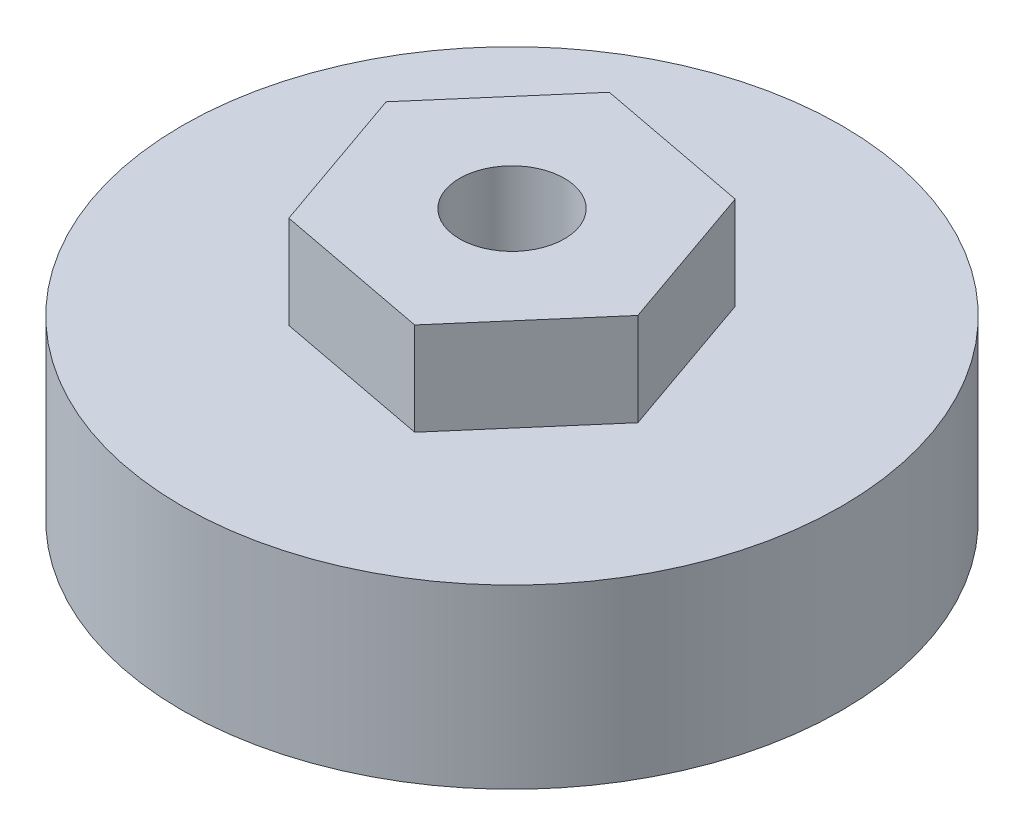
SolidWorks part; units mm, degrees
ref_plane "Front Plane" through (0, 0, 0) normal (0, 0, 1) x (1, 0, 0)
ref_plane "Top Plane" through (0, 0, 0) normal (0, 1, 0) x (1, 0, 0)
ref_plane "Right Plane" through (0, 0, 0) normal (1, 0, 0) x (0, 0, -1)
sketch "Sketch1" plane through (0, 0, 0) normal (0, 1, 0) x (1, 0, 0)
  circle A0 centre (0, 0) radius 11
  dimension "D1" = 22
extrude "Boss-Extrude1" add sketch "Sketch1" along normal blind 9
sketch "Sketch2" plane through (0, 9, 0) normal (0, 1, 0) x (1, 0, 0)
  line L1 (3.4477, 3.9981) -> (-1.7386, 4.9848)
  line L2 (-1.7386, 4.9848) -> (-5.1863, 0.9867)
  line L3 (-5.1863, 0.9867) -> (-3.4477, -3.9981)
  line L4 (-3.4477, -3.9981) -> (1.7386, -4.9848)
  line L5 (1.7386, -4.9848) -> (5.1863, -0.9867)
  line L6 (5.1863, -0.9867) -> (3.4477, 3.9981)
  circle A0 centre (0, 0) radius 4.572 construction
  dimension "D1" = 9.144
extrude "Cut-Extrude1" cut sketch "Sketch2" against normal blind 3.1 flip side to cut
sketch "Sketch3" plane through (0, 9, 0) normal (0, 1, 0) x (1, 0, 0)
  circle A0 centre (0, 0) radius 1.75
  dimension "D1" = 3.5
extrude "Cut-Extrude2" cut sketch "Sketch3" against normal through all
sketch "Sketch4" plane through (0, 5.9, 0) normal (0, 1, 0) x (1, 0, 0)
  point P0 (0, 0)
equation "\"MDF\"= 4.8mm"
equation "\"Foamcore\"= 4.6mm"
equation "\"PCB\" = 1.6mm"
equation "\"GMaterial\"= \"MDF\""
equation "\"BaseWidth\" = 10in"
equation "\"SkidLength\" = 1in"
equation "\"SkidClearance\" = 0.4in"
equation "\"MotorMountLength\" = 2in"
equation "\"MotorMountWidth\" = \"GMaterial\""
equation "\"MotorMountHeight\" = 2.25in"
equation "\"UnoStackWidth\" = 77.4mm"
equation "\"UnoStackLength\" = 79.8mm"
equation "\"UnoStackHeight\" = 34.2mm"
equation "\"TallHexRiserHeight\" = 22.2mm"
equation "\"PingPongBallSize\" = 40mm"
equation "\"BarrelLength\" = 9in"
equation "\"BarrelSize\" = \"PingPongBallSize\""
equation "\"PlatformLength\" = 4in"
equation "\"PlatformWidth\" = 6in"
equation "\"ServoMountHeight\"=2.49223"
equation "\"ServoGearHeight\" = 0.95330261in"
equation "\"ServoMountLength\"= 1.53774"
equation "\"PivotHoleRadius\"= 0.616358"
equation "\"PlatformMountHeight\" = 3.19"
equation "\"TensionOffSet\"= .3mm"
equation "\"MotorMountWedge\"=0.333333"
equation "\"LaserCutterOffset\"= .3mm"
equation "\"BumperWidth\"=11"
equation "\"PitcherWheelCompression\" = 2.5mm"
equation "\"PitchingWheelWidth\" = 26.2mm"
equation "\"PitchingWheelDiameter\" = 65.5mm"
equation "\"PitchingWheelMountOffset\" = 8.4mm"
equation "\"PitchingWheelInnerDiameter\" = 45.5mm"
equation "\"PitchingWheelBoltShoulder\" = 4.5mm"
equation "\"BrassCouplingLength\" = 18mm"
equation "\"PitchingMotorHeight\" = 57.0mm"
equation "\"PitchingMotorShaftTopHeight\" = \"PitchingMotorHeight\" - 44.1mm"
equation "\"PitchingMotorBodyHeight\" = 38mm"
equation "\"PitchingMotorTopShoulderHeight\" = 40.6mm - \"PitchingMotorBodyHeight\" "
equation "\"PitchingMotorBottomShoulderHeight\" = 40.2mm - \"PitchingMotorBodyHeight\""
equation "\"PitchingMotorBottomShaftHeight\" = \"PitchingMotorHeight\" - \"PitchingMotorShaftTopHeight\" - \"PitchingMotorTopShoulderHeight\" - \"PitchingMotorBodyHeight\" - \"PitchingMotorBottomShoulderHeight\""
equation "\"PitchingMotorShaftDiameter\" = 2.2mm"
equation "\"PitchingMotorBodyDiameter\" = 27.4mm"
equation "\"PitchingMotorTopShoulderDiameter\" = 9.8mm"
equation "\"PitchingMotorBottomShoulderDiameter\" = 9.8mm"
equation "\"BrassCouplingHexSize\" = 12mm"
equation "\"BrassCouplingBoreSize\" = 3.17mm"
equation "\"PitchingMotorMountingHoleDistance\" = 16mm"
equation "\"Acrylic\" = 4.4mm"
equation "\"WheelDiameter\"=2.99213"
equation "\"PitchingMotorDistance\" = \"PitchingWheelDiameter\" + \"PingPongBallSize\" - \"PitcherWheelCompression\"*2"
equation "\"PitchingMotorPlatformOffset\"=1"
equation "\"ServoPlatformOffset\"=1.64173"
equation "\"BallBearingDiameter\" = 22mm"
equation "\"BallBearingWidth\" = 9mm"
equation "\"BallBearingHexShoulder\" = 9mm - 5.9mm"
equation "\"D1@Sketch1\"=\"BallBearingDiameter\""
equation "\"D1@Boss-Extrude1\"=\"BallBearingWidth\""
equation "\"BallBearingHexSize\" = .36in"
equation "\"D1@Sketch2\"=\"BallBearingHexSize\""
equation "\"D1@Cut-Extrude1\"=\"BallBearingHexShoulder\""
equation "\"D1@Sketch3\"=3.5mm"
